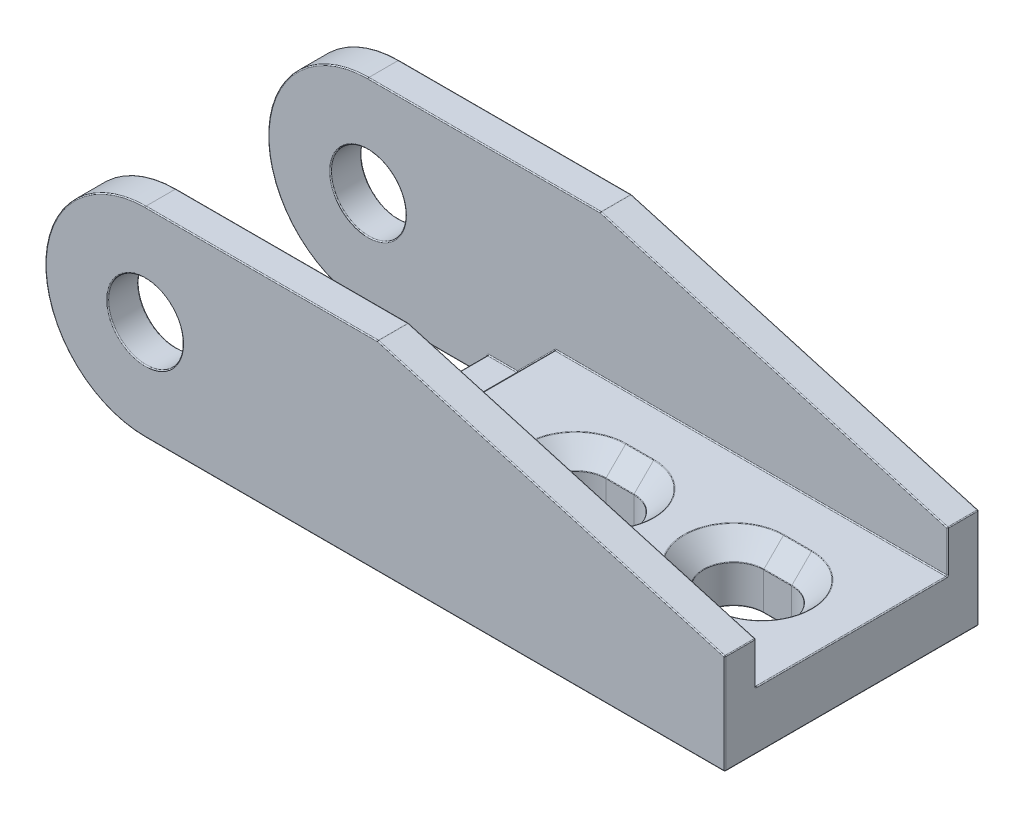
SolidWorks part; units mm, degrees
ref_plane "Front Plane" through (0, 0, 0) normal (0, 0, 1) x (1, 0, 0)
ref_plane "Top Plane" through (0, 0, 0) normal (0, 1, 0) x (1, 0, 0)
ref_plane "Right Plane" through (0, 0, 0) normal (1, 0, 0) x (0, 0, -1)
sketch "Sketch1" plane through (0, 0, 0) normal (0, 1, 0) x (1, 0, 0)
  line L0 (5.6, 0) -> (7, 0) construction
  line L1 (-11.5, -4.8) -> (11.5, -4.8)
  line L2 (-11.5, -4.8) -> (-11.5, 4.8)
  line L3 (-11.5, 4.8) -> (11.5, 4.8)
  line L4 (11.5, -4.8) -> (11.5, 4.8)
  line L5 (0, 4.8) -> (0, -4.8) construction
  line L6 (-11.5, 0) -> (11.5, 0) construction
  line L7 (5.6, 1.5) -> (7, 1.5)
  line L8 (5.6, -1.5) -> (7, -1.5)
  line L9 (-2.3, 0) -> (-0.9, 0) construction
  line L10 (-2.3, 1.5) -> (-0.9, 1.5)
  line L11 (-2.3, -1.5) -> (-0.9, -1.5)
  arc A0 (5.6, 1.5) -> (5.6, -1.5) centre (5.6, 0) ccw
  arc A1 (7, -1.5) -> (7, 1.5) centre (7, 0) ccw
  arc A2 (-2.3, 1.5) -> (-2.3, -1.5) centre (-2.3, 0) ccw
  arc A3 (-0.9, -1.5) -> (-0.9, 1.5) centre (-0.9, 0) ccw
  point P0 (0, 0)
  point P6 (6.3, 0)
  point P11 (-1.6, 0)
  dimension "D4" = 4.4
  dimension "D5" = 3
  dimension "D1" = 23
  dimension "D2" = 9.6
  dimension "D3" = 3
  dimension "D6" = 7.9
extrude "Boss-Extrude1" add sketch "Sketch1" along normal blind 2.9
chamfer "Chamfer1" distance 1 angle 45 8 edges at (4.1, 2.9, 0) (6.3, 2.9, 1.5) (6.3, 2.9, -1.5) (8.5, 2.9, 0) (-3.8, 2.9, 0) (-1.6, 2.9, 1.5) (-1.6, 2.9, -1.5) (0.6, 2.9, 0)
sketch "Sketch4" plane through (0, 0, 4.8) normal (0, 0, 1) x (1, 0, 0)
  line L0 (-11.5, 1) -> (-10, 1)
  line L1 (-11.5, 2.9) -> (-11.5, 0) construction
  line L2 (-10, 1) -> (-8.1, 2.9)
  line L3 (-11.5, 2.9) -> (11.5, 2.9) construction
  line L4 (-8.1, 2.9) -> (-11.5, 2.9)
  line L5 (-11.5, 2.9) -> (-11.5, 1)
  line L6 (-11.5, 0) -> (11.5, 0) construction
  dimension "D1" = 1
  dimension "D2" = 1.5
  dimension "D3" = 45
extrude "Cut-Extrude1" cut sketch "Sketch4" against normal through all
sketch "Sketch2" plane through (0, 0, 4.8) normal (0, 0, 1) x (1, 0, 0)
  line L0 (11.5, 0) -> (11.5, 5)
  line L1 (11.5, 5) -> (-5.8649, 10)
  line L2 (-5.8649, 10) -> (-17.5, 10)
  line L3 (-11.5, 0) -> (11.5, 0) construction
  line L4 (-17.5, 0) -> (11.5, 0)
  line L5 (8.5, 5) -> (-17.5, 5) construction
  arc A2 (-17.5, 10) -> (-17.5, 0) centre (-17.5, 5) ccw
  circle A3 centre (-17.5, 5) radius 1.875
  dimension "D1" = 17.3649
  dimension "D4" = 3.75
  dimension "D2" = 10
  dimension "D3" = 5
  dimension "D5" = 29
extrude "Boss-Extrude2" add sketch "Sketch2" along normal blind 1.55
mirror "Mirror1" about plane through (0, 0, 0) normal (0, 0, 1) of "Boss-Extrude2"
fillet "Fillet1" radius 0.05 66 edges at (-15.625, 5, -4.8) (-15.625, 5, -6.35) (-14.5, 0, -4.8) (-22.5, 5, -4.8) (2.8175, 7.5, -4.8) (11.5, 3.95, -4.8) (-3, 0, -6.35) (-22.5, 5, -6.35) (-11.6825, 10, -6.35) (2.8175, 7.5, -6.35) (11.5, 2.5, -6.35) (11.5, 5, -5.575) (-5.8649, 10, -5.575) (-15.625, 5, 4.8) (-15.625, 5, 6.35) (-14.5, 0, 4.8) (11.5, 3.95, 4.8) (2.8175, 7.5, 4.8) (-11.6825, 10, 4.8) (-22.5, 5, 4.8) (-3, 0, 6.35) (11.5, 2.5, 6.35) (2.8175, 7.5, 6.35) (-11.6825, 10, 6.35) (-22.5, 5, 6.35) (-5.8649, 10, 5.575) (11.5, 5, 5.575) (-10.75, 1, 4.8) (-9.05, 1.95, 4.8) (-10.75, 1, -4.8) (-9.05, 1.95, -4.8) (-11.5, 1, 0) (-10, 1, 0) (-8.1, 2.9, 0) (-3.8, 0, 0) (-1.6, 0, 1.5) (0.6, 0, 0) (-1.6, 0, -1.5) (4.1, 0, 0) (6.3, 0, 1.5) (8.5, 0, 0) (6.3, 0, -1.5) (11.5, 0, 0) (-11.5, 0, 0) (11.5, 2.9, 0) (1.7, 2.9, -4.8) (1.7, 2.9, 4.8) (-11.5, 0.5, 4.8) (-11.5, 0.5, -4.8) (4.1, 1.9, 0) (1.6, 2.9, 0) (-1.6, 2.9, -2.5) (-1.6, 2.9, 2.5) (-4.8, 2.9, 0) (9.5, 2.9, 0) (6.3, 2.9, -2.5) (6.3, 2.9, 2.5) (3.1, 2.9, 0) (6.3, 1.9, 1.5) (6.3, 1.9, -1.5) (8.5, 1.9, 0) (-3.8, 1.9, 0) (-1.6, 1.9, 1.5) (-1.6, 1.9, -1.5) (0.6, 1.9, 0) (-11.6825, 10, -4.8)
